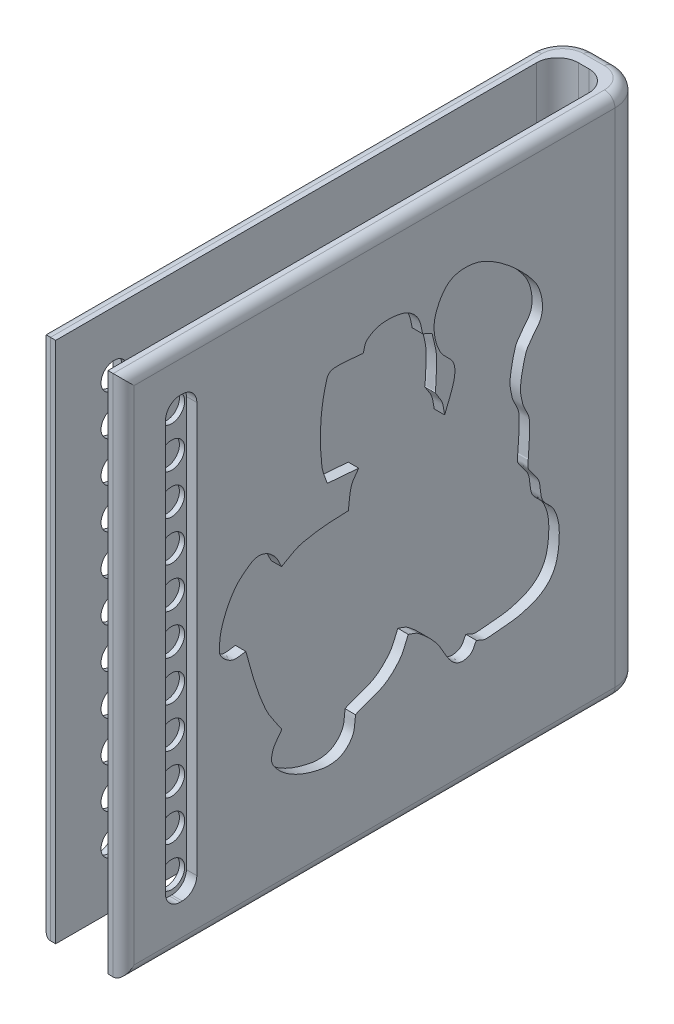
SolidWorks part; units mm, degrees
ref_plane "Front Plane" through (0, 0, 0) normal (0, 0, 1) x (1, 0, 0)
ref_plane "Top Plane" through (0, 0, 0) normal (0, 1, 0) x (1, 0, 0)
ref_plane "Right Plane" through (0, 0, 0) normal (1, 0, 0) x (0, 0, -1)
sketch "Sketch1" plane through (0, 0, 0) normal (0, 0, 1) x (1, 0, 0)
  line L1 (2, -12.5) -> (-2, -12.5)
  line L2 (2, -12.5) -> (2, 12.5)
  line L3 (2, 12.5) -> (-2, 12.5)
  line L4 (-2, -12.5) -> (-2, 12.5)
  line L5 (2, -12.5) -> (-2, 12.5) construction
  line L6 (2, 12.5) -> (-2, -12.5) construction
  point P0 (0, 0)
  dimension "D1" = 4
  dimension "D2" = 25
extrude "Boss-Extrude1" add sketch "Sketch1" along normal blind 25
sketch "Sketch2" plane through (0, 0, 25) normal (0, 0, 1) x (1, 0, 0)
  line L0 (2, 12.5) -> (-2, 12.5) construction
  line L1 (1.25, -12.5) -> (-1.25, -12.5)
  line L2 (1.25, -12.5) -> (1.25, 12.5)
  line L3 (1.25, 12.5) -> (-1.25, 12.5)
  line L4 (-1.25, -12.5) -> (-1.25, 12.5)
  line L5 (1.25, -12.5) -> (-1.25, 12.5) construction
  line L6 (1.25, 12.5) -> (-1.25, -12.5) construction
  point P0 (0, 0)
  dimension "D1" = 2.5
extrude "Cut-Extrude1" cut sketch "Sketch2" against normal blind 24
fillet "Fillet2" radius 1 2 edges at (1.25, 0, 1) (-1.25, 0, 1)
sketch "Sketch3" plane through (-2, 0, 0) normal (-1, 0, 0) x (0, 0, 1)
  line L1 (22.3, 10.5) -> (22.2, 10.5)
  line L2 (23, 9.8) -> (23, -9.8)
  line L3 (22.3, -10.5) -> (22.2, -10.5)
  line L4 (21.5, 9.8) -> (21.5, -9.8)
  arc A0 (21.5, -9.8) -> (22.2, -10.5) centre (22.2, -9.8) ccw
  arc A1 (22.3, -10.5) -> (23, -9.8) centre (22.3, -9.8) ccw
  arc A2 (23, 9.8) -> (22.3, 10.5) centre (22.3, 9.8) ccw
  arc A3 (22.2, 10.5) -> (21.5, 9.8) centre (22.2, 9.8) ccw
  point P14 (23, -10.5)
  point P17 (23, 10.5)
  point P20 (21.5, 10.5)
  dimension "D6" = 0.7
  dimension "D1" = 1.5
extrude "Cut-Extrude2" cut sketch "Sketch3" against normal blind 0.5
sketch "Sketch4" plane through (-1.5, 0, 0) normal (-1, 0, 0) x (0, 0, 1)
  line L0 (23, -9.8) -> (23, 9.8) construction
  circle A0 centre (22.2066, 0) radius 0.625
  dimension "D1" = 1.25
  dimension "D2" = 0.7934
extrude "Cut-Extrude3" cut sketch "Sketch4" against normal up to next
pattern_linear "LPattern1" count 6 spacing 1.93 along (0, -1, 0) count 6 spacing 1.93 along (0, 1, 0) of "Cut-Extrude3"
mirror "Mirror1" about plane through (0, 0, 0) normal (1, 0, 0) of "LPattern1", "Cut-Extrude3", "Cut-Extrude2"
sketch "Sketch6" plane through (0, 0, 0) normal (1, 0, 0) x (0, 0, -1)
  line L0 (-13.7566, 3.2081) -> (-15.2566, 3.3281)
  line L1 (-10.6966, 7.2431) -> (-10.2466, 7.0331)
  spline S0 degree 3 poles (-19.1566, -1.6819) (-19.3616, -1.6969) (-19.5715, -1.7741) (-19.7716, -1.7269) (-19.9511, -1.6845) (-20.1062, -1.5573) (-20.2366, -1.4269) (-20.3283, -1.3352) (-20.4124, -1.2115) (-20.4166, -1.0819) (-20.428, -0.7292) (-20.3898, -0.3678) (-20.2816, -0.0319) (-20.1465, 0.3874) (-19.9535, 0.7952) (-19.6966, 1.1531) (-19.5005, 1.4263) (-19.2243, 1.6383) (-18.9466, 1.8281) (-18.8213, 1.9138) (-18.6632, 1.9704) (-18.5116, 1.9631) (-18.3362, 1.9546) (-18.1565, 1.8892) (-18.0166, 1.7831) (-17.6811, 1.5287) (-17.6019, 1.3009) (-17.4466, 0.9731) knots 0 0 0 0 1 1 1 2 2 2 3 3 3 4 4 4 5 5 5 6 6 6 7 7 7 8 8 8 9 9 9 9
  spline S1 degree 3 poles (-17.4466, 0.9731) (-17.1416, 1.1281) (-16.8621, 1.3498) (-16.5316, 1.4381) (-15.7927, 1.6354) (-15.0161, 1.6724) (-14.2516, 1.6931) knots 0 0 0 0 1 1 1 2 2 2 2
  spline S2 degree 3 poles (-14.2516, 1.6931) (-14.2016, 2.0181) (-14.2037, 2.3555) (-14.1016, 2.6681) (-14.0353, 2.8711) (-13.8716, 3.0281) (-13.7566, 3.2081) knots 0 0 0 0 1 1 1 2 2 2 2
  spline S3 degree 3 poles (-15.2566, 3.3281) (-15.3416, 3.5981) (-15.4781, 3.857) (-15.5116, 4.1381) (-15.5839, 4.7441) (-15.6106, 5.359) (-15.5716, 5.9681) (-15.5353, 6.5349) (-15.4448, 7.1026) (-15.2866, 7.6481) (-15.2492, 7.7771) (-15.135, 7.917) (-15.0016, 7.9331) (-14.5195, 7.9913) (-14.0316, 7.8831) (-13.5466, 7.8581) knots 0 0 0 0 1 1 1 2 2 2 3 3 3 4 4 4 5 5 5 5
  spline S4 degree 3 poles (-13.5466, 7.8581) (-13.4816, 8.0131) (-13.4767, 8.2109) (-13.3516, 8.3231) (-13.1667, 8.4888) (-12.9225, 8.6036) (-12.6766, 8.6381) (-12.334, 8.6862) (-11.9743, 8.6577) (-11.6416, 8.5631) (-11.4122, 8.4978) (-11.1979, 8.3533) (-11.0416, 8.1731) (-10.8045, 7.8998) (-10.762, 7.5702) (-10.6966, 7.2431) knots 0 0 0 0 1 1 1 2 2 2 3 3 3 4 4 4 5 5 5 5
  spline S5 degree 3 poles (-10.2466, 7.0331) (-10.1766, 6.6931) (-10.0595, 6.3595) (-10.0366, 6.0131) (-10.0042, 5.5239) (-10.0622, 5.0329) (-10.0816, 4.5431) (-10.0822, 4.5273) (-10.1039, 4.5121) (-10.0966, 4.4981) (-9.9965, 4.3075) (-9.8456, 4.1433) (-9.7666, 3.9431) (-9.6935, 3.7579) (-9.6866, 3.5531) (-9.6466, 3.3581) knots 0 0 0 0 1 1 1 2 2 2 3 3 3 4 4 4 5 5 5 5
  spline S6 degree 3 poles (-9.6466, 3.3581) (-9.4966, 3.7681) (-9.2885, 4.1613) (-9.1966, 4.5881) (-9.146, 4.8229) (-9.129, 5.0886) (-9.2266, 5.3081) (-9.3608, 5.61) (-9.7007, 5.7818) (-9.8566, 6.0731) (-10.0118, 6.3632) (-10.1086, 6.6907) (-10.1416, 7.0181) (-10.1699, 7.2988) (-10.139, 7.5951) (-10.0366, 7.8581) (-9.9133, 8.1747) (-9.7429, 8.4959) (-9.4816, 8.7131) (-9.2713, 8.888) (-8.975, 8.9611) (-8.7016, 8.9681) (-8.3644, 8.9767) (-8.0173, 8.9006) (-7.7116, 8.7581) (-7.2641, 8.5495) (-6.8571, 8.2536) (-6.4816, 7.9331) (-6.0673, 7.5795) (-5.6797, 7.1866) (-5.3566, 6.7481) (-5.1825, 6.5118) (-5.0697, 6.2258) (-5.0116, 5.9381) (-4.9572, 5.6685) (-4.9381, 5.3735) (-5.0266, 5.1131) (-5.1261, 4.8202) (-5.3824, 4.607) (-5.5516, 4.3481) (-5.6276, 4.2318) (-5.7233, 4.1216) (-5.7616, 3.9881) (-5.8798, 3.5762) (-5.9852, 3.1555) (-6.0166, 2.7281) (-6.0358, 2.4665) (-5.9792, 2.2016) (-5.9116, 1.9481) (-5.8382, 1.6727) (-5.6285, 1.4364) (-5.5966, 1.1531) (-5.5368, 0.6212) (-5.6223, 0.083) (-5.6416, -0.4519) (-5.6423, -0.4725) (-5.6566, -0.4913) (-5.6566, -0.5119) (-5.6566, -0.632) (-5.6923, -0.763) (-5.6416, -0.8719) (-5.5169, -1.1397) (-5.2593, -1.3339) (-5.1466, -1.6069) (-5.0298, -1.8897) (-5.0958, -2.2296) (-4.9666, -2.5069) (-4.8482, -2.7611) (-4.5559, -2.9031) (-4.4266, -3.1519) (-4.285, -3.4243) (-4.1929, -3.7306) (-4.1716, -4.0369) (-4.1421, -4.4623) (-4.1746, -4.8978) (-4.2766, -5.3119) (-4.3429, -5.5812) (-4.4795, -5.8421) (-4.6666, -6.0469) (-4.8611, -6.2599) (-5.1189, -6.4194) (-5.3866, -6.5269) (-5.7636, -6.6783) (-6.1667, -6.7784) (-6.5716, -6.8119) (-7.79, -6.9129) (-7.6522, -6.9766) (-8.1316, -6.7369) knots 0 0 0 0 1 1 1 2 2 2 3 3 3 4 4 4 5 5 5 6 6 6 7 7 7 8 8 8 9 9 9 10 10 10 11 11 11 12 12 12 13 13 13 14 14 14 15 15 15 16 16 16 17 17 17 18 18 18 19 19 19 20 20 20 21 21 21 22 22 22 23 23 23 24 24 24 25 25 25 26 26 26 27 27 27 28 28 28 29 29 29 29
  spline S7 degree 3 poles (-8.1316, -6.7369) (-8.2216, -6.8769) (-8.2644, -7.0627) (-8.4016, -7.1569) (-8.5407, -7.2523) (-8.7309, -7.2935) (-8.8966, -7.2619) (-9.071, -7.2287) (-9.2326, -7.1131) (-9.3466, -6.9769) (-9.6252, -6.644) (-9.7782, -6.2191) (-10.0516, -5.8819) (-10.2966, -5.5798) (-10.5825, -5.3081) (-10.8916, -5.0719) (-11.034, -4.9631) (-11.2216, -4.9319) (-11.3866, -4.8619) knots 0 0 0 0 1 1 1 2 2 2 3 3 3 4 4 4 5 5 5 6 6 6 6
  spline S8 degree 3 poles (-11.3866, -4.8619) (-11.5166, -5.1319) (-11.5949, -5.4336) (-11.7766, -5.6719) (-11.9868, -5.9477) (-12.2436, -6.1995) (-12.5416, -6.3769) (-12.9102, -6.5964) (-13.3442, -6.6803) (-13.7416, -6.8419) (-13.7996, -6.8655) (-13.8516, -6.9019) (-13.9066, -6.9319) knots 0 0 0 0 1 1 1 2 2 2 3 3 3 4 4 4 4
  spline S9 degree 3 poles (-13.9066, -6.9319) (-13.9566, -7.2019) (-13.9264, -7.5001) (-14.0566, -7.7419) (-14.184, -7.9786) (-14.3925, -8.1958) (-14.6416, -8.2969) (-14.9294, -8.4137) (-15.2665, -8.4152) (-15.5716, -8.3569) (-16.0671, -8.2622) (-16.5605, -8.1006) (-16.9966, -7.8469) (-17.3421, -7.646) (-17.6626, -7.3656) (-17.8666, -7.0219) (-17.9713, -6.8456) (-17.9192, -6.6005) (-17.8516, -6.4069) (-17.7683, -6.1686) (-17.5716, -5.9869) (-17.4316, -5.7769) knots 0 0 0 0 1 1 1 2 2 2 3 3 3 4 4 4 5 5 5 6 6 6 7 7 7 7
  spline S10 degree 3 poles (-17.4316, -5.7769) (-17.6866, -5.3769) (-17.9967, -5.0071) (-18.1966, -4.5769) (-18.6251, -3.655) (-18.8946, -2.6643) (-19.1566, -1.6819) knots 0 0 0 0 1 1 1 2 2 2 2
extrude "Cut-Extrude4" cut sketch "Sketch6" against normal blind 0.5 from surface at 2 starting at face at (2, 0, 12.5)
fillet "Fillet3" radius 1.5 2 edges at (-2, 0, 0) (2, 0, 0)
fillet "Fillet4" radius 0.5 12 edges at (2, 12.5, 13.25) (1.5607, 12.5, 0.4393) (0, 12.5, 0) (-1.5607, 12.5, 0.4393) (2, -12.5, 13.25) (1.5607, -12.5, 0.4393) (0, -12.5, 0) (-1.5607, -12.5, 0.4393) (2, 0, 25) (-2, 12.5, 13.25) (-2, -12.5, 13.25) (-2, 0, 25)
